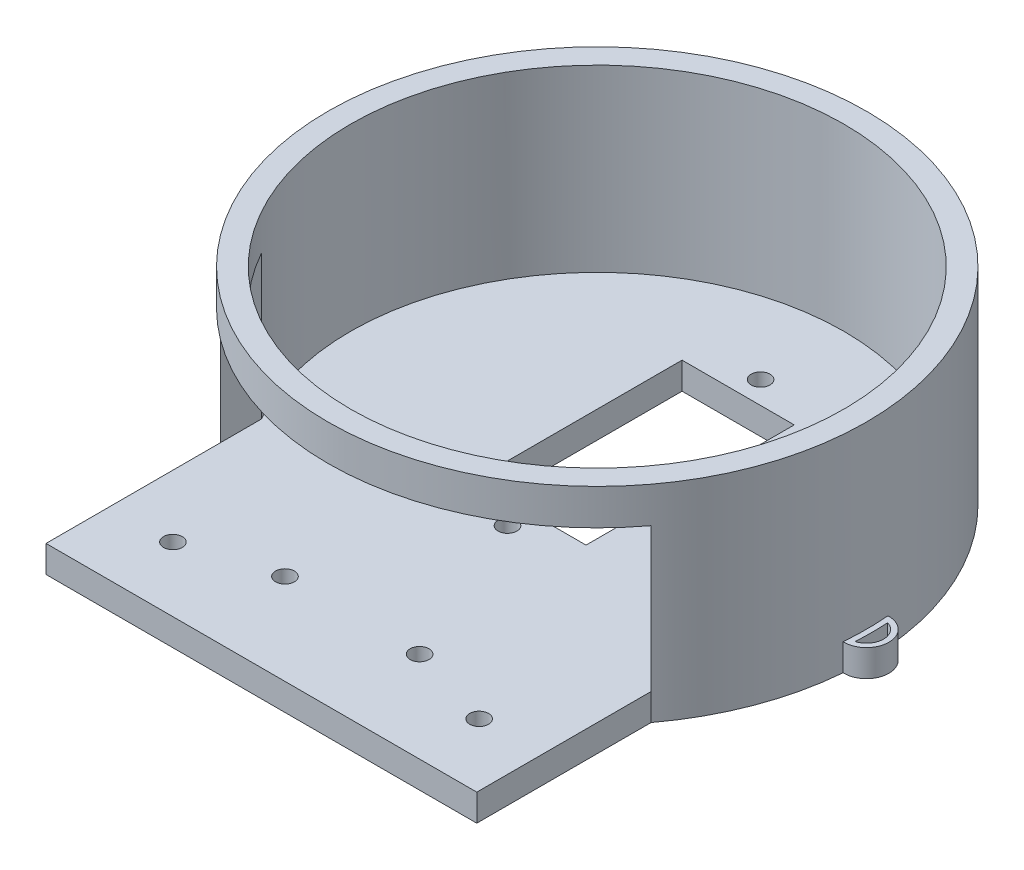
SolidWorks part; units mm, degrees
ref_plane "Front Plane" through (0, 0, 0) normal (0, 0, 1) x (1, 0, 0)
ref_plane "Top Plane" through (0, 0, 0) normal (0, 1, 0) x (1, 0, 0)
ref_plane "Right Plane" through (0, 0, 0) normal (1, 0, 0) x (0, 0, -1)
sketch "Sketch1" plane through (0, 0, 0) normal (0, 1, 0) x (1, 0, 0)
  line L0 (0, 0) -> (0, 31.4) construction
  line L1 (-6.25, 15.7) -> (6.25, 15.7)
  line L2 (-6.25, 15.7) -> (-6.25, -7.5)
  line L3 (-6.25, -7.5) -> (6.25, -7.5)
  line L4 (6.25, 15.7) -> (6.25, -7.5)
  arc A0 (-29.8958, -2.4978) -> (29.8958, -2.4978) centre (0, 0) ccw
  arc A1 (-29.8958, 2.4978) -> (-29.8958, -2.4978) centre (-30, 0) ccw
  arc A2 (2.4978, 29.8958) -> (-2.4978, 29.8958) centre (0, 30) ccw
  arc A3 (29.8958, 2.4978) -> (29.8958, -2.4978) centre (30, 0) cw
  arc A4 (-2.4978, 29.8958) -> (-29.8958, 2.4978) centre (0, 0) ccw
  arc A5 (29.8958, 2.4978) -> (2.4978, 29.8958) centre (0, 0) ccw
  point P7 (0, -7.5)
  point P9 (0, 15.7)
  dimension "D1" = 60
  dimension "D5" = 2.5
  dimension "D2" = 23.2
  dimension "D3" = 12.5
  dimension "D4" = 7.5
extrude "Boss-Extrude1" add sketch "Sketch1" along normal blind 3
sketch "Sketch4" plane through (0, 3, 0) normal (0, 1, 0) x (1, 0, 0)
  circle A0 centre (0, 0) radius 30
  arc A1 (-2.4978, 29.8958) -> (-29.8958, 2.4978) centre (0, 0) ccw construction
  circle A3 centre (0, 0) radius 27.5
  dimension "D1" = 2.5
extrude "Boss-Extrude3" add sketch "Sketch4" along normal blind 20
sketch "Sketch5" plane through (0, 3, 0) normal (0, 1, 0) x (1, 0, 0)
  line L0 (0, 20.9719) -> (0, -12.9053) construction
  line L3 (6.25, 15.7) -> (-6.25, 15.7) construction
  line L4 (-6.25, 4.1) -> (6.25, 4.1) construction
  line L5 (-6.25, 15.7) -> (-6.25, -7.5) construction
  line L6 (6.25, -7.5) -> (6.25, 15.7) construction
  circle A0 centre (0, 18.2) radius 1.05
  circle A1 centre (0, -10) radius 1.05
  dimension "D1" = 2.1
  dimension "D3" = 2.5
extrude "Cut-Extrude2" cut sketch "Sketch5" against normal through all
sketch "Sketch6" plane through (0, 0, 0) normal (0, 1, 0) x (1, 0, 0)
  line L0 (-21, -21.4243) -> (-21, -34.4243)
  line L1 (-21, -34.4243) -> (21, -34.4243)
  line L2 (21, -34.4243) -> (21, -21.4243)
  circle A0 centre (0, 0) radius 30 construction
  circle A2 centre (0, 0) radius 30
  arc A3 (-21, -21.4243) -> (21, -21.4243) centre (0, 0) ccw
  dimension "D2" = 42
  dimension "D3" = 13
  dimension "D4" = 0
extrude "Boss-Extrude4" add sketch "Sketch6" along normal blind 3 contours L0 L1 L2 A3
ref_plane "Plane2" through (0, 0, 21.4243) normal (0, 0, -1) x (-1, 0, 0)
sketch "Sketch9" plane through (0, 0, 21.4243) normal (0, 0, -1) x (-1, 0, 0)
  line L0 (24, 3) -> (24, 19)
  line L1 (24, 19) -> (-24, 19)
  line L2 (-24, 19) -> (-24, 3)
  line L3 (24, 3) -> (-24, 3)
  line L4 (0, 0) -> (0, 29.4968) construction
  line L5 (21, 3) -> (-21, 3) construction
  point P2 (0, 19)
  dimension "D1" = 16
  dimension "D2" = 48
extrude "Cut-Extrude11" cut sketch "Sketch9" along normal up to next and the other way up to next
sketch "Sketch10" plane through (0, 3, 0) normal (0, 1, 0) x (1, 0, 0)
  line L0 (0, 0) -> (0, -34.4243) construction
  line L1 (-21, -31.4243) -> (0, -25.0039) construction
  line L2 (0, -25.0039) -> (21, -31.4243) construction
  line L3 (-21, -34.4243) -> (21, -34.4243) construction
  line L4 (-21, -21.4243) -> (-21, -34.4243) construction
  line L5 (21, -34.4243) -> (21, -21.4243) construction
  circle A1 centre (-7.5, -27.2969) radius 1.05
  circle A2 centre (-17.063, -30.2206) radius 1.05
  circle A3 centre (7.5, -27.2969) radius 1.05
  circle A4 centre (17.063, -30.2206) radius 1.05
  point P10 (-17.063, -30.2206)
  point P11 (-7.5, -27.2969)
  point P12 (7.5, -27.2969)
  point P13 (17.063, -30.2206)
  dimension "D4" = 2.1
  dimension "D1" = 17
  dimension "D2" = 10
  dimension "D3" = 15
  dimension "D5" = 3
sketch "Sketch12" plane through (0, 3, 0) normal (0, 1, 0) x (1, 0, 0)
  arc A6 (1.8199, 30.5458) -> (-1.8199, 30.5458) centre (0, 0) ccw
  arc A7 (1.8199, 30.5458) -> (-1.8199, 30.5458) centre (0, 30) ccw
  arc A8 (1.8199, 30.5458) -> (-1.8199, 30.5458) centre (0, 0) ccw
  arc A9 (1.8199, 30.5458) -> (-1.8199, 30.5458) centre (0, 30) ccw
  arc A12 (30.5458, -1.8199) -> (30.5458, 1.8199) centre (0, 0) ccw
  arc A13 (30.5458, -1.8199) -> (30.5458, 1.8199) centre (30, 0) ccw
  arc A14 (30.5458, -1.8199) -> (30.5458, 1.8199) centre (0, 0) ccw
  arc A15 (30.5458, -1.8199) -> (30.5458, 1.8199) centre (30, 0) ccw
  arc A18 (-30.5458, 1.8199) -> (-30.5458, -1.8199) centre (0, 0) ccw
  arc A19 (-30.5458, 1.8199) -> (-30.5458, -1.8199) centre (-30, 0) ccw
  arc A20 (-30.5458, 1.8199) -> (-30.5458, -1.8199) centre (0, 0) ccw
  arc A21 (-30.5458, 1.8199) -> (-30.5458, -1.8199) centre (-30, 0) ccw
  dimension "D1" = 0.6
  dimension "D2" = 0.6
  dimension "D3" = 0.6
extrude "Cut-Extrude12" cut sketch "Sketch12" against normal through all
sketch "Sketch13" plane through (0, 3, 0) normal (0, 1, 0) x (1, 0, 0)
  line L4 (21, -34.4243) -> (21, -21.4243)
  line L5 (-21, -34.4243) -> (21, -34.4243)
  line L6 (-21, -21.4243) -> (-21, -34.4243)
  line L7 (21, -34.4243) -> (21, -21.4243)
  line L8 (-21, -34.4243) -> (21, -34.4243)
  line L9 (-21, -21.4243) -> (-21, -34.4243)
  line L10 (24, -37.4243) -> (24, -21.4243)
  line L11 (-24, -37.4243) -> (24, -37.4243)
  line L12 (-24, -21.4243) -> (-24, -37.4243)
  line L13 (24, -37.4243) -> (24, -18)
  line L14 (-24, -37.4243) -> (24, -37.4243)
  line L15 (-24, -18) -> (-24, -37.4243)
  arc A0 (-29.8958, -2.4978) -> (-21, -21.4243) centre (0, 0) ccw construction
  arc A3 (21, -21.4243) -> (29.8958, -2.4978) centre (0, 0) ccw construction
  arc A11 (-2.4978, 29.8958) -> (-29.8958, 2.4978) centre (0, 0) ccw
  arc A12 (2.4978, 29.8958) -> (-2.4978, 29.8958) centre (0, 30) ccw
  arc A13 (29.8958, 2.4978) -> (2.4978, 29.8958) centre (0, 0) ccw
  arc A14 (29.8958, -2.4978) -> (29.8958, 2.4978) centre (30, 0) ccw
  arc A15 (21, -21.4243) -> (29.8958, -2.4978) centre (0, 0) ccw
  arc A16 (-29.8958, -2.4978) -> (-21, -21.4243) centre (0, 0) ccw
  arc A17 (-29.8958, 2.4978) -> (-29.8958, -2.4978) centre (-30, 0) ccw
  arc A22 (21, -21.4243) -> (24, -18) centre (0, 0) ccw
  arc A23 (-24, -18) -> (-21, -21.4243) centre (0, 0) ccw
  dimension "D1" = 3
  dimension "D2" = 0
extrude "Boss-Extrude8" add sketch "Sketch13" against normal blind 3
extrude "Cut-Extrude13" cut sketch "Sketch10" against normal through all
